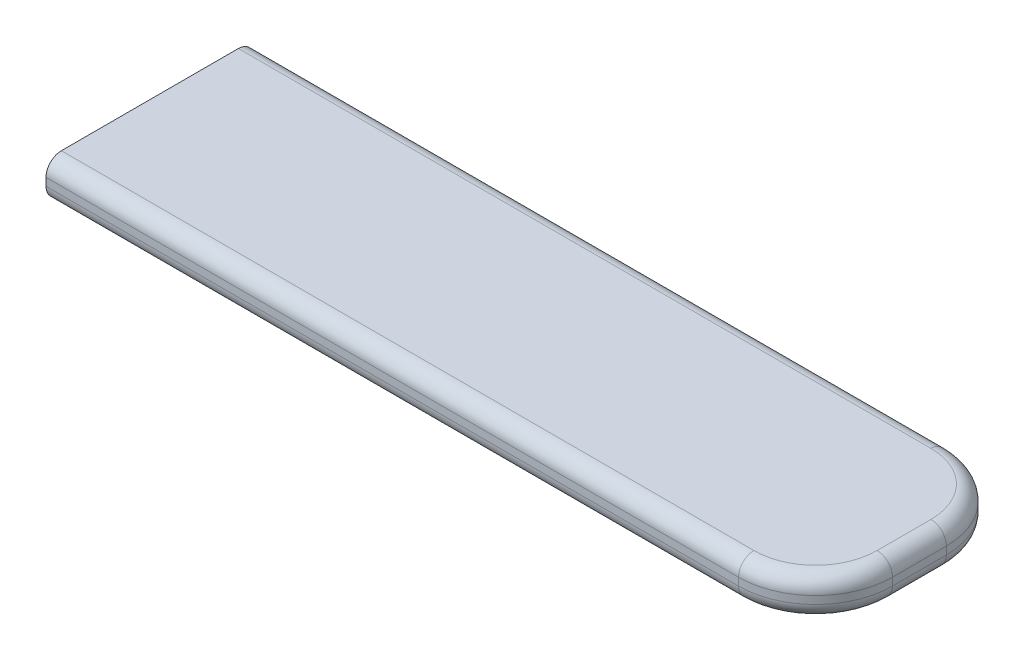
SolidWorks part; units mm, degrees
ref_plane "Front Plane" through (0, 0, 0) normal (0, 0, 1) x (1, 0, 0)
ref_plane "Top Plane" through (0, 0, 0) normal (0, 1, 0) x (1, 0, 0)
ref_plane "Right Plane" through (0, 0, 0) normal (1, 0, 0) x (0, 0, -1)
sketch "Sketch1" plane through (0, 0, 0) normal (0, 1, 0) x (1, 0, 0)
  line L0 (0, 0) -> (0, 270)
  line L1 (0, 0) -> (-1000, 0)
  line L3 (0, 270) -> (-1000, 270)
  line L4 (-1000, 0) -> (-1000, 270)
  dimension "D1" = 1000
  dimension "D2" = 270
extrude "Boss-Extrude1" add sketch "Sketch1" along normal blind 50 contours L1 L4 L3 L0
fillet "Fillet1" radius 100 2 edges at (0, 25, -270) (0, 25, 0)
fillet "Fillet2" radius 20 10 edges at (-550, 0, -270) (-29.2893, 0, -240.7107) (0, 0, -135) (-29.2893, 0, -29.2893) (-550, 50, -270) (-29.2893, 50, -240.7107) (0, 50, -135) (-29.2893, 50, -29.2893) (-550, 0, 0) (-550, 50, 0)
